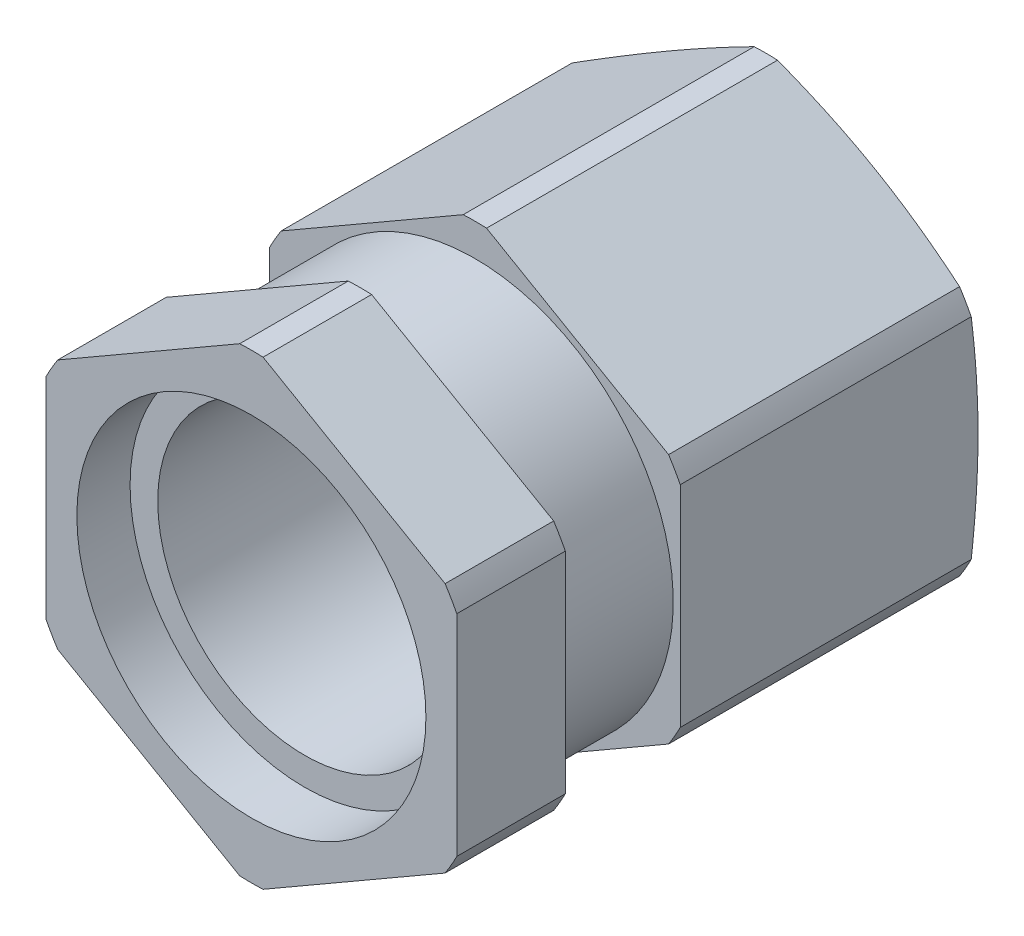
SolidWorks part; units mm, degrees
material "K1045"
ref_plane "Front Plane" through (0, 0, 0) normal (0, 0, 1) x (1, 0, 0)
ref_plane "Top Plane" through (0, 0, 0) normal (0, 1, 0) x (1, 0, 0)
ref_plane "Right Plane" through (0, 0, 0) normal (1, 0, 0) x (0, 0, -1)
sketch "Sketch1" plane through (0, 0, 0) normal (1, 0, 0) x (0, 0, -1)
  line L0 (0, 0) -> (-13.6593, 0) construction
  line L1 (0, 0) -> (0, 3.5)
  line L2 (0, 3.5) -> (-0.5145, 5.42)
  line L3 (-0.5145, 5.42) -> (-7.35, 5.42)
  line L4 (-7.35, 5.42) -> (-7.35, 4.66)
  line L5 (-7.35, 4.66) -> (-10.05, 4.66)
  line L6 (-10.05, 4.66) -> (-10.05, 5.42)
  line L7 (-10.05, 5.42) -> (-12.6, 5.42)
  line L8 (-12.6, 5.42) -> (-12.6, 4.1)
  line L9 (-12.6, 4.1) -> (-11.35, 4.1)
  line L10 (-11.35, 4.1) -> (-11.35, 3.45)
  line L11 (-11.35, 3.45) -> (-6.5, 3.45)
  line L12 (-6.5, 3.45) -> (-6.5, 1.5)
  line L13 (-6.5, 1.5) -> (-4.8013, 1.5)
  line L14 (-4.8013, 1.5) -> (-3.9, 0)
  line L15 (0, 0) -> (-3.9, 0)
  dimension "D1" = 59
  dimension "D2" = 10.84
  dimension "D3" = 7
  dimension "D4" = 15
  dimension "D5" = 12.6
  dimension "D6" = 9.32
  dimension "D7" = 2.55
  dimension "D8" = 2.7
  dimension "D9" = 8.2
  dimension "D10" = 6.9
  dimension "D11" = 3
  dimension "D12" = 6.1
  dimension "D13" = 8.7
  dimension "D14" = 1.25
revolve "Revolve1" add sketch "Sketch1" angle 360 about L0
cosmetic thread "Cosmetic Thread1" parameters "D2"=7.5
sketch "Sketch2" plane through (0, 0, 0) normal (0, 0, -1) x (-1, 0, 0)
  line L1 (4.825, 2.7857) -> (0, 5.5714)
  line L2 (0, 5.5714) -> (-4.825, 2.7857)
  line L3 (-4.825, 2.7857) -> (-4.825, -2.7857)
  line L4 (-4.825, -2.7857) -> (0, -5.5714)
  line L5 (0, -5.5714) -> (4.825, -2.7857)
  line L6 (4.825, -2.7857) -> (4.825, 2.7857)
  circle A0 centre (0, 0) radius 4.825 construction
  dimension "D1" = 9.65
extrude "Extrude2" cut sketch "Sketch2" against normal through all flip side to cut
